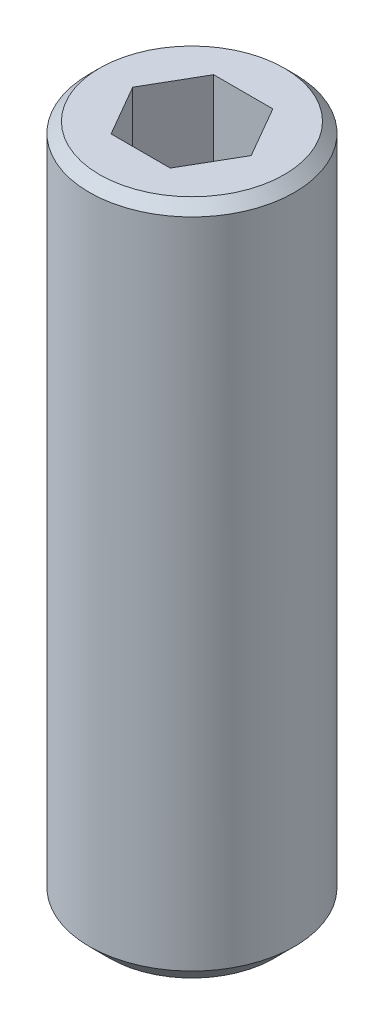
SolidWorks part; units mm, degrees
material "acero"
ref_plane "Alzado" through (0, 0, 0) normal (0, 0, 1) x (1, 0, 0)
ref_plane "Planta" through (0, 0, 0) normal (0, 1, 0) x (1, 0, 0)
ref_plane "Vista lateral" through (0, 0, 0) normal (1, 0, 0) x (0, 0, -1)
sketch "Croquis1" plane through (0, 0, 0) normal (0, 0, 1) x (1, 0, 0)
  line L0 (0, 0) -> (0, -60.9498) construction
  line L1 (0, 0) -> (1.5, 0)
  line L4 (1.5, 0) -> (1.5, -10)
  line L5 (1.5, -10) -> (0, -10)
  line L6 (0, -10) -> (0, 0)
  dimension "D1" = 10
  dimension "D4" = 3
revolve "Revolución1" add sketch "Croquis1" angle 360 about L0
sketch "Croquis3" plane through (0, 0, 0) normal (0, 1, 0) x (1, 0, 0)
  line L1 (-0.433, 0.75) -> (-0.866, 0)
  line L2 (-0.866, 0) -> (-0.433, -0.75)
  line L3 (-0.433, -0.75) -> (0.433, -0.75)
  line L4 (0.433, -0.75) -> (0.866, 0)
  line L5 (0.866, 0) -> (0.433, 0.75)
  line L6 (0.433, 0.75) -> (-0.433, 0.75)
  circle A0 centre (0, 0) radius 0.75 construction
  dimension "D1" = 1.5
extrude "Cortar-Extruir2" cut sketch "Croquis3" against normal blind 1.5
chamfer "Chaflán3" distance 0.3 angle 45 1 edges at (0, -10, 1.5)
chamfer "Chaflán4" distance 0.15 angle 45 1 edges at (0, 0, 1.5)
